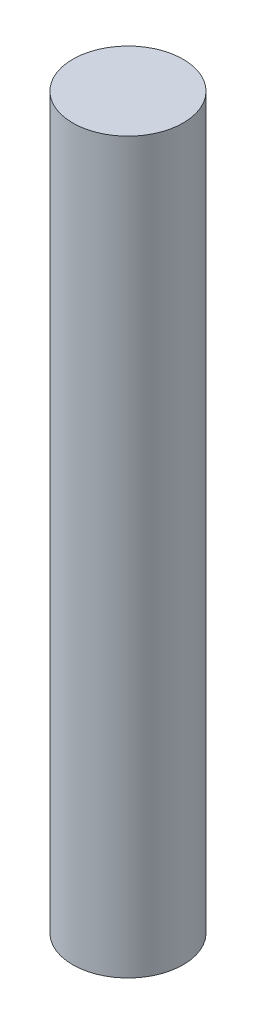
SolidWorks part; units mm, degrees
ref_plane "Front Plane" through (0, 0, 0) normal (0, 0, 1) x (1, 0, 0)
ref_plane "Top Plane" through (0, 0, 0) normal (0, 1, 0) x (1, 0, 0)
ref_plane "Right Plane" through (0, 0, 0) normal (1, 0, 0) x (0, 0, -1)
sketch "Sketch1" plane through (0, 0, 0) normal (0, 1, 0) x (1, 0, 0)
  circle A0 centre (0, 0) radius 2.5
  dimension "D1" = 5
extrude "Boss-Extrude1" add sketch "Sketch1" along normal blind 33
